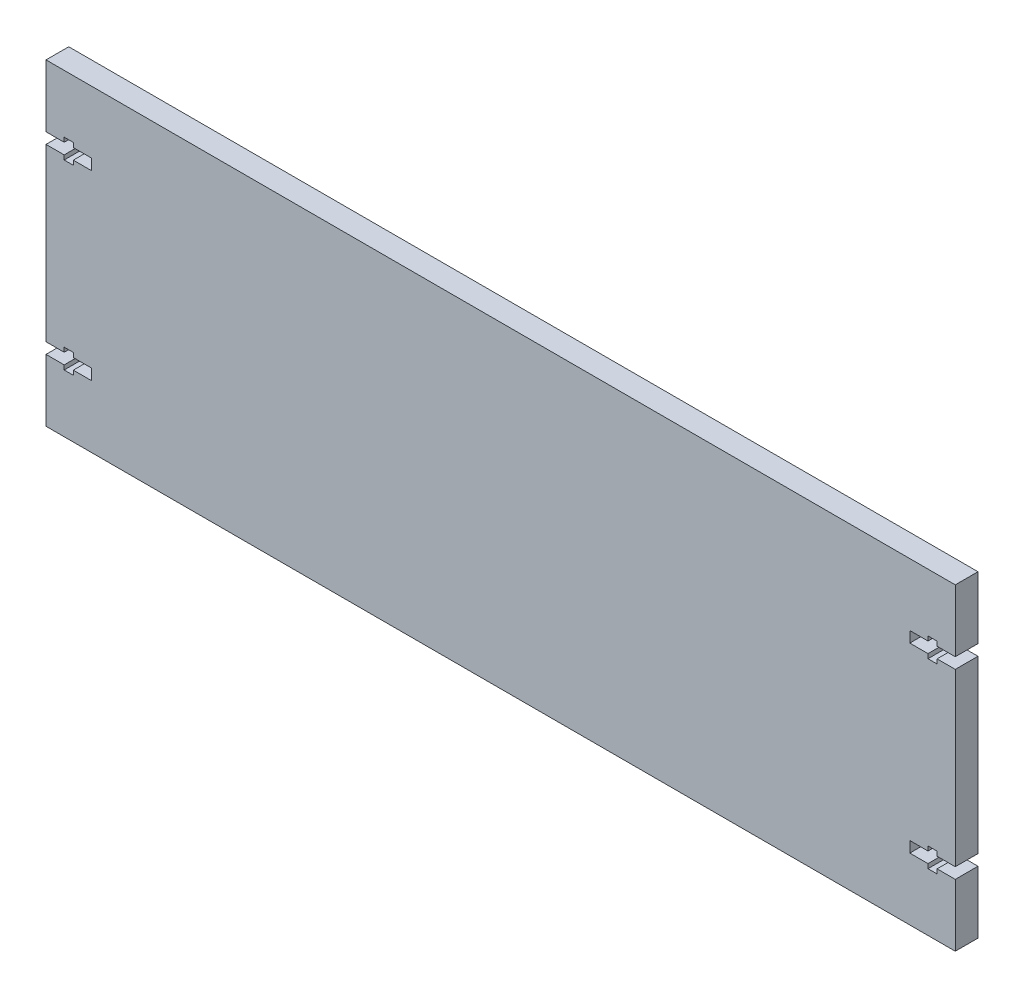
SolidWorks part; units mm, degrees
material "Acrylic (Medium-high impact)"
ref_plane "Front Plane" through (0, 0, 0) normal (0, 0, 1) x (1, 0, 0)
ref_plane "Top Plane" through (0, 0, 0) normal (0, 1, 0) x (1, 0, 0)
ref_plane "Right Plane" through (0, 0, 0) normal (1, 0, 0) x (0, 0, -1)
sketch "Sketch1" plane through (0, 0, 0) normal (0, 0, 1) x (1, 0, 0)
  line L0 (0, 44.323) -> (254, 44.323) construction
  line L1 (0, 0) -> (254, 0)
  line L2 (0, 0) -> (0, 88.646)
  line L3 (0, 88.646) -> (254, 88.646)
  line L4 (254, 0) -> (254, 88.646)
  line L5 (127, 88.646) -> (127, 0) construction
  line L6 (5.08, 21.6852) -> (7.62, 21.6853)
  line L7 (0, 18.923) -> (12.7, 18.923) construction
  line L8 (0, 18.923) -> (0, 17.399)
  line L9 (0, 17.399) -> (12.7, 17.399)
  line L10 (12.7, 20.447) -> (12.7, 17.399)
  line L11 (5.08, 18.923) -> (7.62, 18.923) construction
  line L12 (5.08, 21.6852) -> (5.08, 16.1608)
  line L13 (5.08, 16.1608) -> (7.62, 16.1608)
  line L14 (7.62, 21.6853) -> (7.62, 16.1608)
  line L15 (0, 20.447) -> (12.7, 20.447)
  line L16 (12.7, 68.199) -> (12.7, 71.247)
  line L17 (7.62, 66.9608) -> (7.62, 72.4853)
  line L18 (5.08, 66.9608) -> (5.08, 72.4853)
  line L19 (5.08, 72.4853) -> (7.62, 72.4853)
  line L20 (0, 71.247) -> (12.7, 71.247)
  line L21 (0, 69.723) -> (12.7, 69.723) construction
  line L22 (5.08, 66.9608) -> (7.62, 66.9608)
  line L23 (0, 68.199) -> (12.7, 68.199)
  line L24 (246.38, 21.6852) -> (246.38, 16.1608)
  line L25 (248.92, 21.6852) -> (248.92, 16.1608)
  line L26 (241.3, 68.199) -> (241.3, 71.247)
  line L27 (246.38, 66.9608) -> (246.38, 72.4853)
  line L28 (248.92, 66.9608) -> (248.92, 72.4853)
  line L29 (248.92, 66.9608) -> (246.38, 66.9608)
  line L30 (254, 68.199) -> (241.3, 68.199)
  line L31 (254, 69.723) -> (241.3, 69.723) construction
  line L32 (254, 71.247) -> (241.3, 71.247)
  line L33 (248.92, 72.4853) -> (246.38, 72.4853)
  line L34 (241.3, 20.447) -> (241.3, 17.399)
  line L35 (254, 20.447) -> (241.3, 20.447)
  line L36 (254, 17.399) -> (241.3, 17.399)
  line L37 (254, 18.923) -> (241.3, 18.923) construction
  line L38 (248.92, 21.6852) -> (246.38, 21.6852)
  line L39 (248.92, 16.1608) -> (246.38, 16.1608)
  point P9 (0, 18.923)
  dimension "D1" = 88.646
  dimension "D2" = 254
  dimension "D3" = 25.4
  dimension "D4" = 5.5245
  dimension "D5" = 12.7
  dimension "D6" = 3.048
  dimension "D7" = 2.54
  dimension "D8" = 5.08
extrude "Boss-Extrude1" add sketch "Sketch1" along normal blind 6.35 contours L2 L15 L12 L6 L14 L10 L9 L13 L1 L4 L3
